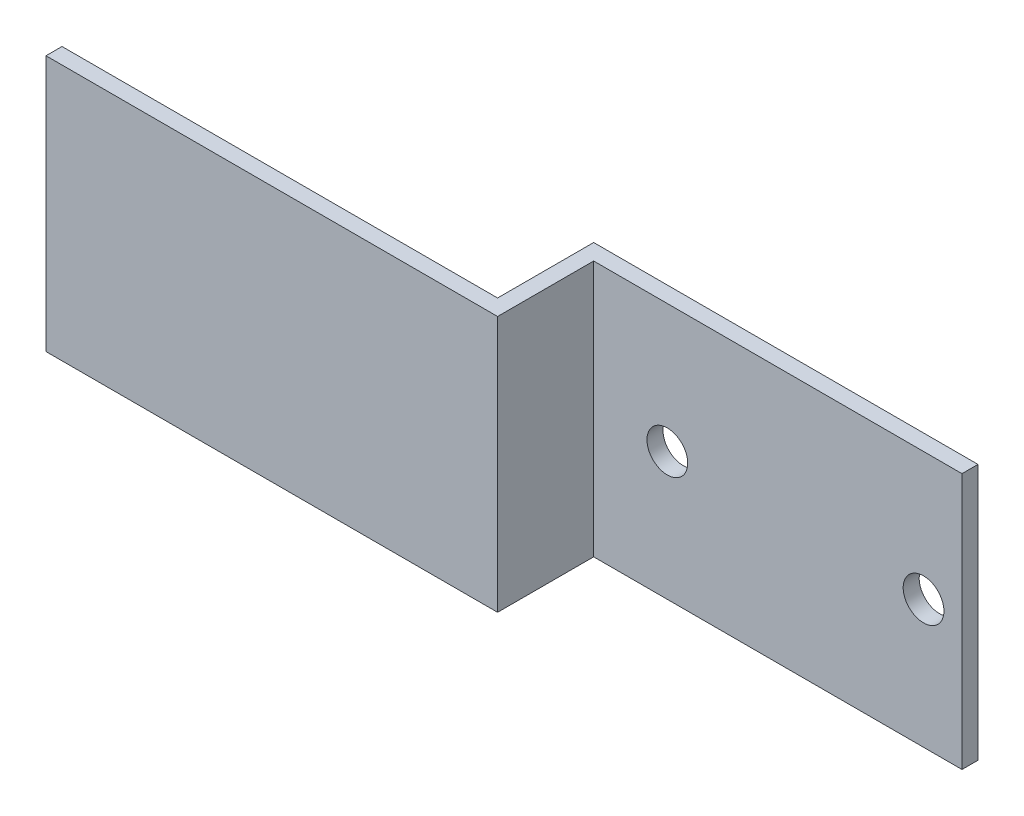
SolidWorks part; units mm, degrees
material "1060 Alloy"
ref_plane "Front Plane" through (0, 0, 0) normal (0, 0, 1) x (1, 0, 0)
ref_plane "Top Plane" through (0, 0, 0) normal (0, 1, 0) x (1, 0, 0)
ref_plane "Right Plane" through (0, 0, 0) normal (1, 0, 0) x (0, 0, -1)
sketch "Sketch1" plane through (0, 0, 0) normal (0, 0, 1) x (1, 0, 0)
  line L0 (0, 0) -> (38.1, 0)
  line L1 (38.1, 0) -> (38.1, 25.4)
  line L2 (38.1, 25.4) -> (0, 25.4)
  line L3 (0, 25.4) -> (0, 0)
  dimension "D1" = 38.1
  dimension "D2" = 25.4
extrude "Boss-Extrude1" add sketch "Sketch1" along normal blind 1.5875
sketch "Sketch3" plane through (0, 0, 0) normal (-1, 0, 0) x (0, 0, 1)
  line L0 (1.5875, 0) -> (11.1125, 0)
  line L1 (11.1125, 0) -> (11.1125, 25.4)
  line L2 (11.1125, 25.4) -> (1.5875, 25.4)
  line L3 (1.5875, 25.4) -> (1.5875, 0)
  dimension "D1" = 9.525
extrude "Boss-Extrude2" add sketch "Sketch3" against normal blind 1.5875
sketch "Sketch4" plane through (0, 0, 11.1125) normal (0, 0, 1) x (1, 0, 0)
  line L0 (0, 0) -> (-43.18, 0)
  line L1 (-43.18, 0) -> (-43.18, 25.4)
  line L2 (-43.18, 25.4) -> (0, 25.4)
  line L3 (0, 25.4) -> (0, 0)
  dimension "D1" = 43.18
extrude "Boss-Extrude3" add sketch "Sketch4" against normal blind 1.5875
sketch "Sketch2" plane through (0, 0, 1.5875) normal (0, 0, 1) x (1, 0, 0)
  line L0 (38.1, 0) -> (38.1, 25.4) construction
  line L2 (38.1, 25.4) -> (1.5875, 25.4) construction
  circle A0 centre (34.29, 12.7) radius 2.0193
  dimension "D1" = 4.0386
  dimension "D2" = 3.81
  dimension "D3" = 12.7
extrude "Cut-Extrude1" cut sketch "Sketch2" against normal blind 2.54
pattern_linear "LPattern1" count 2 spacing 25.4 along (-1, 0, 0) of "Cut-Extrude1"
sketch "Sketch5" plane through (0, 0, 11.1125) normal (0, 0, 1) x (1, 0, 0)
  line L0 (-43.18, 25.4) -> (-43.18, 0) construction
  line L1 (1.5875, 25.4) -> (-43.18, 25.4) construction
  circle A0 centre (-40.005, 12.7) radius 2.0193
  dimension "D1" = 4.0386
  dimension "D2" = 3.175
  dimension "D3" = 12.7
extrude "Cut-Extrude2" [suppressed] cut sketch "Sketch5" against normal up to surface (1.5875 mm away)
